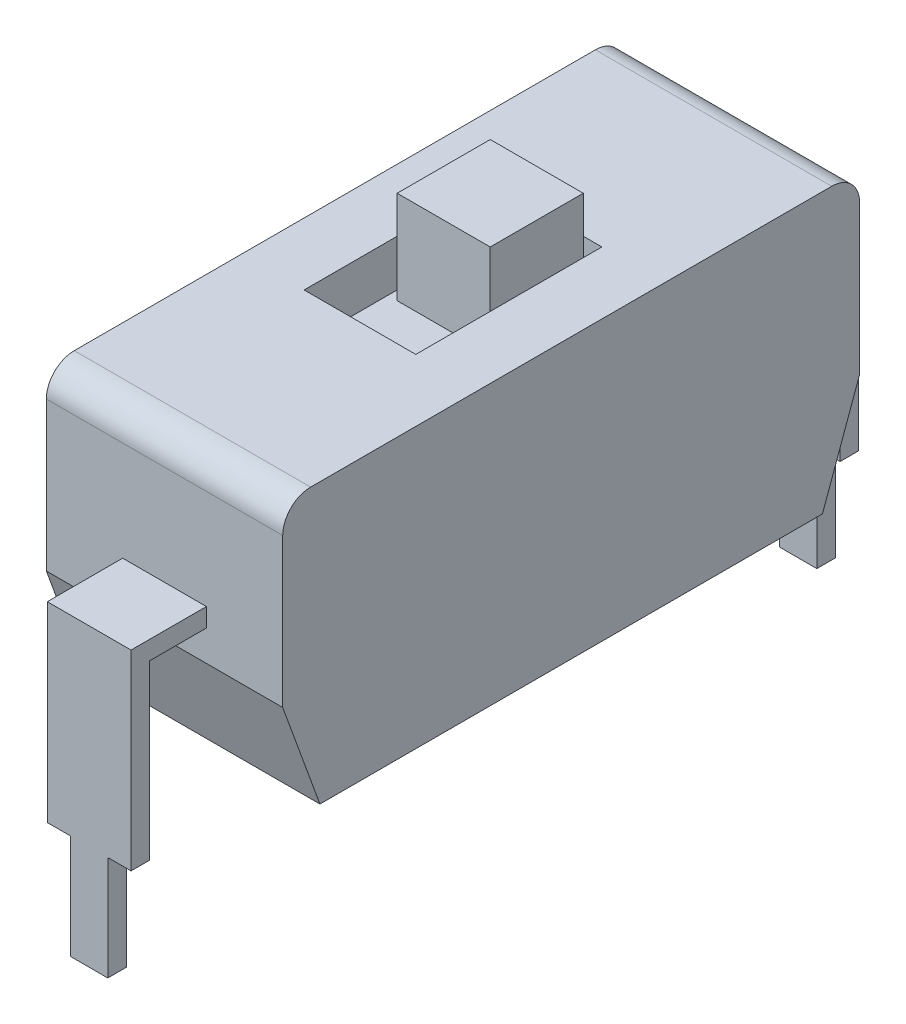
SolidWorks part; units mm, degrees
ref_plane "前视基准面" through (0, 0, 0) normal (0, 0, 1) x (1, 0, 0)
ref_plane "上视基准面" through (0, 0, 0) normal (0, 1, 0) x (1, 0, 0)
ref_plane "右视基准面" through (0, 0, 0) normal (1, 0, 0) x (0, 0, -1)
sketch "草图1" plane through (0, 0, 0) normal (0, 1, 0) x (1, 0, 0)
  line L0 (-25.8641, 0) -> (23.6912, 0) construction
  line L1 (-1.27, 3.1) -> (1.27, 3.1)
  line L2 (-1.27, 3.1) -> (-1.27, -3.1)
  line L3 (-1.27, -3.1) -> (1.27, -3.1)
  line L4 (1.27, 3.1) -> (1.27, -3.1)
  line L5 (0, 27.0034) -> (0, -30.5011) construction
  dimension "D1" = 2.54
  dimension "D2" = 6.2
extrude "拉伸1" add sketch "草图1" along normal blind 3
sketch "草图2" plane through (0, 3, 0) normal (0, 1, 0) x (1, 0, 0)
  line L0 (0, 4.1013) -> (0, -4.9096) construction
  line L1 (-0.6, 1) -> (0.6, 1)
  line L2 (-0.6, 1) -> (-0.6, -1)
  line L3 (-0.6, -1) -> (0.6, -1)
  line L4 (0.6, 1) -> (0.6, -1)
  line L5 (-2.6262, 0) -> (2.5723, 0) construction
  dimension "D1" = 2
  dimension "D2" = 1.2
extrude "切除-拉伸1" cut sketch "草图2" against normal blind 0.5
sketch "草图3" plane through (0, 2.5, 0) normal (0, 1, 0) x (1, 0, 0)
  line L0 (0, 1.6905) -> (0, -2.2591) construction
  line L1 (-0.5, 0.9) -> (0.5, 0.9)
  line L2 (-0.5, 0.9) -> (-0.5, -0.1)
  line L3 (-0.5, -0.1) -> (0.5, -0.1)
  line L4 (0.5, 0.9) -> (0.5, -0.1)
  line L5 (0.6, 1) -> (-0.6, 1) construction
  dimension "D1" = 1
  dimension "D2" = 1
  dimension "D3" = 0.1
extrude "凸台-拉伸1" add sketch "草图3" along normal blind 1
fillet "圆角1" radius 0.3 2 edges at (0, 3, -3.1) (0, 3, 3.1)
chamfer "倒角1" distance 0.4 angle 70 2 edges at (0, 0, -3.1) (0, 0, 3.1)
sketch "草图4" plane through (0, 0, 0) normal (1, 0, 0) x (0, 0, -1)
  line L0 (-2.8054, 1.6286) -> (-3.91, 1.6286)
  line L1 (-3.91, 1.6286) -> (-3.91, -1.5487)
  line L2 (-3.91, -1.5487) -> (-3.71, -1.5487)
  line L3 (-3.71, -1.5487) -> (-3.71, 1.4286)
  line L4 (-3.71, 1.4286) -> (-2.8054, 1.4286)
  line L5 (-2.8054, 1.4286) -> (-2.8054, 1.6286)
  line L6 (-3.81, 2.0606) -> (-3.81, -2.2733) construction
  line L7 (3.81, 2.0606) -> (3.81, -2.2733) construction
  line L8 (0, 5.0891) -> (0, -2.8492) construction
  line L9 (2.8054, 1.4286) -> (2.8054, 1.6286)
  line L10 (3.71, 1.4286) -> (2.8054, 1.4286)
  line L11 (3.71, -1.5487) -> (3.71, 1.4286)
  line L12 (3.91, -1.5487) -> (3.71, -1.5487)
  line L13 (3.91, 1.6286) -> (3.91, -1.5487)
  line L14 (2.8054, 1.6286) -> (3.91, 1.6286)
  dimension "D1" = 0.2
  dimension "D2" = 0.2
  dimension "D3" = 7.62
extrude "凸台-拉伸2" add sketch "草图4" along normal blind 0.45 and the other way blind 0.45
sketch "草图5" plane through (0, 0, 3.91) normal (0, 0, 1) x (1, 0, 0)
  line L0 (0, -2.241) -> (0, 4.4134) construction
  line L1 (0.2, -1.5487) -> (0.2, -0.4271)
  line L2 (-0.45, -1.5487) -> (-0.2, -1.5487)
  line L3 (-0.45, -1.5487) -> (-0.45, -0.4271)
  line L4 (-0.45, -0.4271) -> (-0.2, -0.4271)
  line L5 (-0.2, -1.5487) -> (-0.2, -0.4271)
  line L6 (0.45, -0.4271) -> (0.2, -0.4271)
  line L7 (0.45, -1.5487) -> (0.45, -0.4271)
  line L8 (0.45, -1.5487) -> (0.2, -1.5487)
  dimension "D1" = 0.4
extrude "切除-拉伸2" cut sketch "草图5" against normal through all
